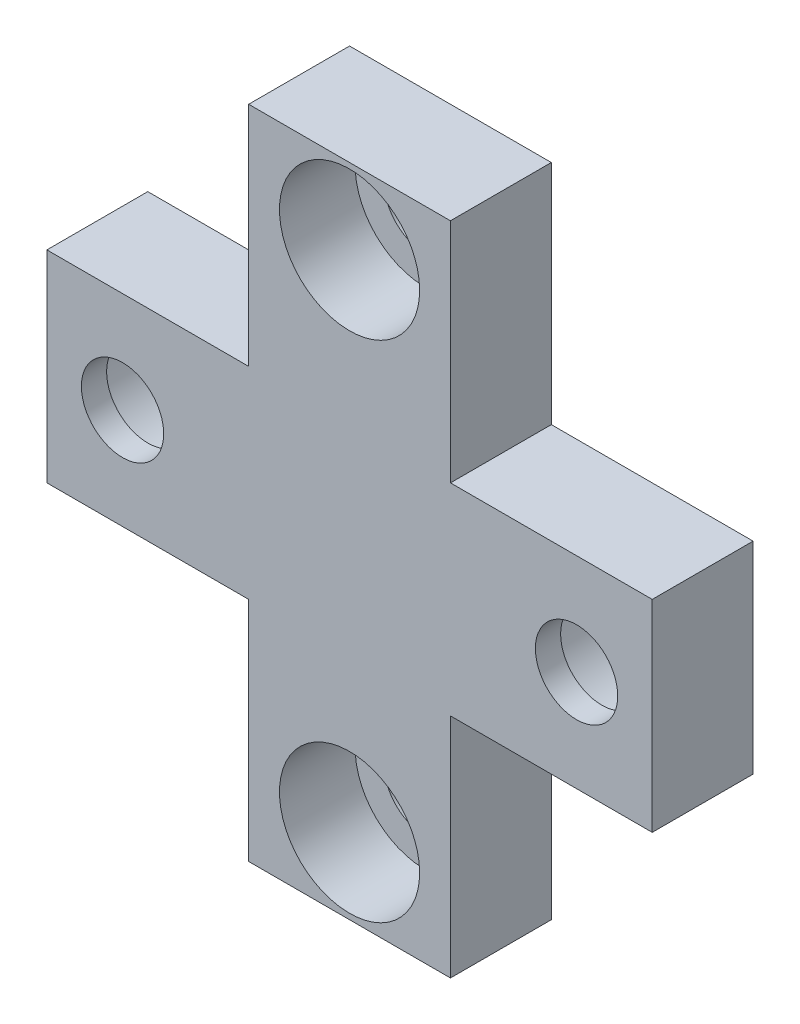
SolidWorks part; units mm, degrees
ref_plane "Front Plane" through (0, 0, 0) normal (0, 0, 1) x (1, 0, 0)
ref_plane "Top Plane" through (0, 0, 0) normal (0, 1, 0) x (1, 0, 0)
ref_plane "Right Plane" through (0, 0, 0) normal (1, 0, 0) x (0, 0, -1)
sketch "Sketch3" plane through (0, 0, 0) normal (0, 0, 1) x (1, 0, 0)
  line L0 (-5, -13) -> (13, -13) construction
  line L1 (0, 0) -> (8, 0)
  line L2 (0, 0) -> (0, -26)
  line L4 (8, 0) -> (8, -26)
  line L5 (-8, -9) -> (16, -9)
  line L6 (-8, -9) -> (-8, -17)
  line L7 (-8, -17) -> (16, -17)
  line L8 (16, -9) -> (16, -17)
  line L9 (4, -3) -> (4, -23) construction
  line L10 (8, -26) -> (0, -26)
  circle A0 centre (-5, -13) radius 1
  circle A1 centre (13, -13) radius 1
  circle A2 centre (4, -3) radius 1
  circle A3 centre (4, -23) radius 1
  point P13 (4, 0)
  point P14 (4, -9)
  point P16 (16, -13)
  point P18 (16, -9.6384)
  point P20 (4, -13)
  dimension "D6" = 2
  dimension "D1" = 18
  dimension "D2" = 8
  dimension "D3" = 8
  dimension "D5" = 3
  dimension "D4" = 9
  dimension "D7" = 9
  dimension "D8" = 20
  dimension "D9" = 26
extrude "Boss-Extrude1" add sketch "Sketch3" along normal blind 4 contours L2 L5 L4 L1 A2 | L5 L2 L10 L4 A3 | L8 L5 L4 L7 A1 | L6 L7 L2 L5 A0 | L2 L7 L4 L5
hole_wizard "CBORE for #4 Socket Head Cap Screw2" positions "3DSketch1" profile "Sketch7" counterbore size "#4" standard "ANSI Inch" end condition through all
sketch3d "3DSketch1"
  line L0 (4, -3, 4) -> (4, -3, 0) construction
  line L1 (4, -23, 4) -> (4, -23, 0) construction
  point P0 (4, -3, 4)
  point P4 (4, -23, 4)
sketch "Sketch7" plane through (4, -3, 4) normal (1, 0, 0) x (0, -1, 0)
  line L0 (0, 0) -> (0, 4)
  line L1 (0, 4) -> (1.6319, 4)
  line L3 (1.6319, 4) -> (1.6319, 3)
  line L4 (1.6319, 3) -> (2.7788, 3)
  line L5 (2.7788, 3) -> (2.7788, 0)
  line L7 (2.7788, 0) -> (0, 0)
  line L11 (0, -6.35) -> (0, 107.95) construction
  dimension "Thru Hole Dia." = 3.2639
  dimension "Thru Hole Depth" = 4
  dimension "C'Bore Dia." = 5.5575
  dimension "C'Bore Depth" = 3
hole_wizard "CBORE for #4 Socket Head Cap Screw3" positions "3DSketch2" profile "Sketch8" counterbore size "#4" standard "ANSI Inch" end condition through all
sketch3d "3DSketch2"
  line L0 (13, -13, 4) -> (13, -13, 0) construction
  line L1 (-5, -13, 4) -> (-5, -13, 0) construction
  point P0 (13, -13, 0)
  point P4 (-5, -13, 0)
sketch "Sketch8" plane through (13, -13, 0) normal (1, 0, 0) x (0, 1, 0)
  line L0 (0, 0) -> (0, 4)
  line L1 (0, 4) -> (1.6319, 4)
  line L3 (1.6319, 4) -> (1.6319, 3)
  line L4 (1.6319, 3) -> (2.7788, 3)
  line L5 (2.7788, 3) -> (2.7788, 0)
  line L7 (2.7788, 0) -> (0, 0)
  line L11 (0, -6.35) -> (0, 107.95) construction
  dimension "Thru Hole Dia." = 3.2639
  dimension "Thru Hole Depth" = 4
  dimension "C'Bore Dia." = 5.5575
  dimension "C'Bore Depth" = 3
equation "\"D7@Sketch3\"=\"D4@Sketch3\""
equation "\"D5@Sketch3\"=(\"D9@Sketch3\"-\"D8@Sketch3\")/2"
